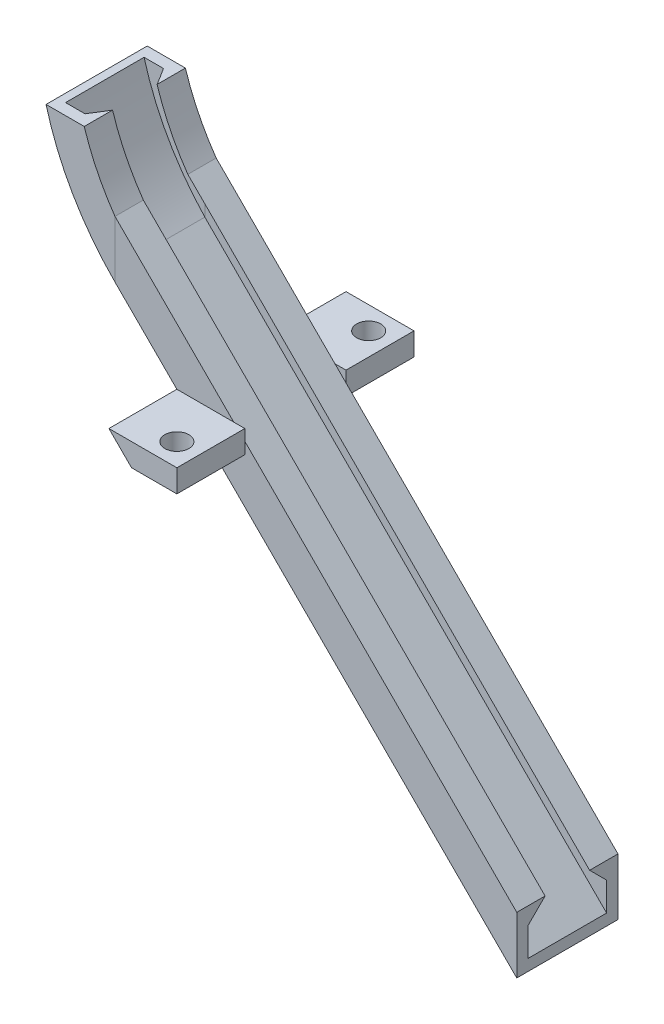
SolidWorks part; units mm, degrees
material "ABS"
ref_plane "Front" through (0, 0, 0) normal (0, 0, 1) x (1, 0, 0)
ref_plane "Top" through (0, 0, 0) normal (0, 1, 0) x (1, 0, 0)
ref_plane "Right" through (0, 0, 0) normal (1, 0, 0) x (0, 0, -1)
sketch "Sketch1" plane through (0, 0, 0) normal (0, 0, 1) x (1, 0, 0)
  line L0 (-126.7315, 126.7315) -> (-112.5893, 112.5893) construction
  line L1 (-126.7315, 126.7315) -> (-131.9079, 146.05) construction
  line L2 (50, 0) -> (-50, 0) construction
  line L3 (-112.5893, 112.5893) -> (0, 0)
  arc A0 (-131.9079, 146.05) -> (-112.5893, 112.5893) centre (-59.8102, 165.3685) ccw
  dimension "D1" = 45
  dimension "D2" = 75
  dimension "D3" = 146.05
  dimension "D4" = 20
sketch "Sketch2" plane through (0, 0, 0) normal (1, 0, 0) x (0, 0, -1)
  line L0 (0, 0) -> (14.175, 0)
  line L1 (50, 0) -> (-50, 0) construction
  line L2 (14.175, 0) -> (14.175, 15.9375)
  line L4 (11, 11.175) -> (11, 3.175)
  line L5 (11, 3.175) -> (-11, 3.175)
  line L6 (-11, 3.175) -> (-11, 11.175)
  line L8 (-14.175, 15.9375) -> (-14.175, 0)
  line L9 (-14.175, 0) -> (0, 0)
  line L10 (-11, 3.175) -> (-11, 0) construction
  line L11 (-14.175, 15.9375) -> (-6.2375, 15.9375)
  line L12 (-6.2375, 15.9375) -> (-11, 11.175)
  line L13 (14.175, 15.9375) -> (6.2375, 15.9375)
  line L14 (6.2375, 15.9375) -> (11, 11.175)
  line L15 (-11, 7.175) -> (-14.175, 7.175) construction
  line L16 (11, 7.175) -> (14.175, 7.175) construction
  dimension "D1" = 22
  dimension "D2" = 8
  dimension "D3" = 3.175
  dimension "D4" = 135
  dimension "D5" = 4.7625
sweep "Sweep1" add profiles "Sketch2" path "Sketch1"
sketch "Sketch3" plane through (0, 0, 14.175) normal (0, 0, -1) x (-1, 0, 0)
  line L8 (131.9079, 146.05) -> (121.2084, 146.05)
  line L9 (121.2084, 146.05) -> (123.9391, 159.8523)
  line L11 (123.9391, 159.8523) -> (131.9079, 146.05)
  arc A0 (112.5893, 128.5268) -> (123.9391, 159.8523) centre (59.8102, 165.3685) ccw construction
extrude "Cut-Extrude1" cut sketch "Sketch3" along normal through all
sketch "Sketch10" plane through (0, 0, 14.175) normal (0, 0, 1) x (1, 0, 0)
  line L0 (-88.9, 88.9) -> (-95.25, 95.25)
  line L2 (-95.25, 95.25) -> (-76.2, 95.25)
  line L3 (-112.5893, 112.5893) -> (0, 0) construction
  line L4 (-76.2, 95.25) -> (-76.2, 88.9)
  line L5 (-76.2, 88.9) -> (-88.9, 88.9)
  dimension "D1" = 6.35
  dimension "D2" = 12.7
  dimension "D3" = 88.9
extrude "Boss-Extrude3" add sketch "Sketch10" along normal blind 19.05
hole_wizard "1/4 Clearance Hole1" positions "Sketch11" profile "Sketch12" hole size "1/4" standard "ANSI Inch" end condition up to next
sketch "Sketch11" plane through (0, 95.25, 0) normal (0, 1, 0) x (1, 0, 0)
  line L0 (-82.55, -26.875) -> (-76.2, -26.875) construction
  line L1 (-76.2, -33.225) -> (-76.2, -14.175) construction
  line L3 (-82.55, -26.875) -> (-82.55, -33.225) construction
  line L4 (-76.2, -33.225) -> (-95.25, -33.225) construction
  point P0 (-82.55, -26.875)
  dimension "D1" = 6.35
sketch "Sketch12" plane through (-82.55, 95.25, 26.875) normal (1, 0, 0) x (0, 0, 1)
  line L0 (0, 0) -> (0, 6.35)
  line L1 (0, 6.35) -> (3.3782, 6.35)
  line L2 (3.3782, 6.35) -> (3.3782, 0)
  line L5 (3.3782, 0) -> (0, 0)
  line L11 (0, -6.35) -> (0, 107.95) construction
  dimension "Thru Hole Dia." = 6.7564
  dimension "Thru Hole Depth" = 6.35
mirror "Mirror1" about plane through (0, 0, 0) normal (0, 0, 1) of "1/4 Clearance Hole1", "Boss-Extrude3"
